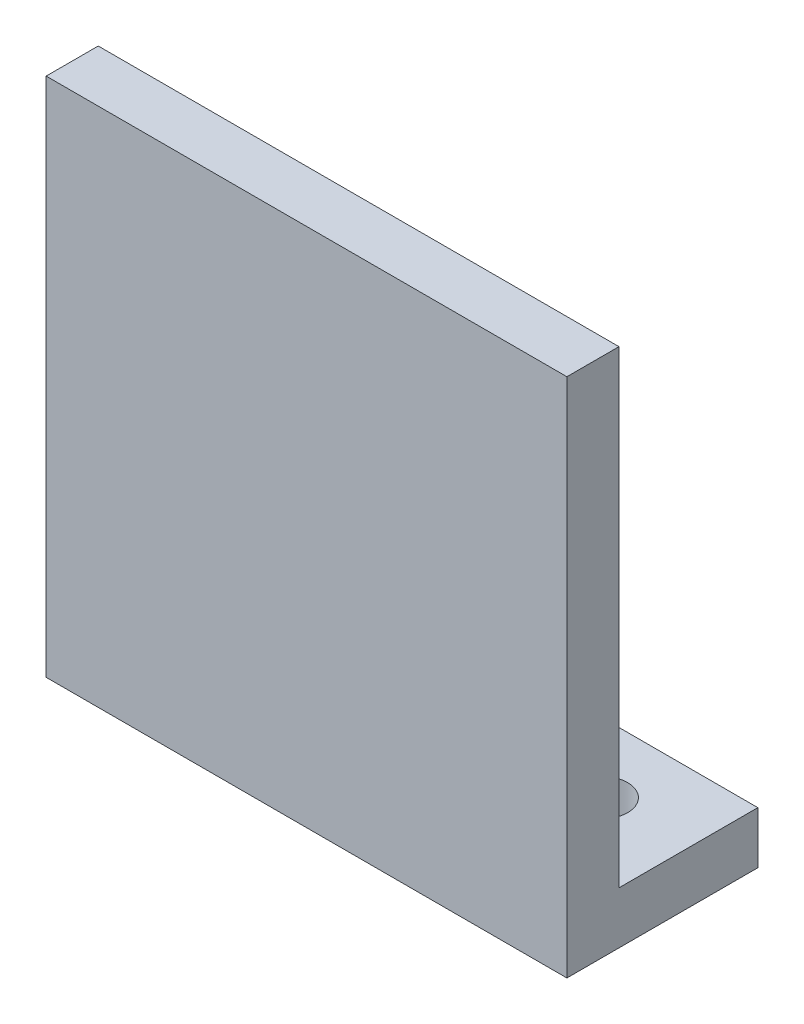
SolidWorks part; units mm, degrees
ref_plane "前视基准面" through (0, 0, 0) normal (0, 0, 1) x (1, 0, 0)
ref_plane "上视基准面" through (0, 0, 0) normal (0, 1, 0) x (1, 0, 0)
ref_plane "右视基准面" through (0, 0, 0) normal (1, 0, 0) x (0, 0, -1)
sketch "草图1" plane through (0, 0, 0) normal (0, 0, 1) x (1, 0, 0)
  line L1 (-15, -15) -> (15, -15)
  line L2 (-15, -15) -> (-15, 15)
  line L3 (-15, 15) -> (15, 15)
  line L4 (15, -15) -> (15, 15)
  line L5 (-15, -15) -> (15, 15) construction
  line L6 (-15, 15) -> (15, -15) construction
  point P0 (0, 0)
  dimension "D1" = 30
  dimension "D2" = 30
extrude "凸台-拉伸1" add sketch "草图1" along normal blind 3 contours L2 L3 L4 L1
sketch "草图2" plane through (0, 0, 0) normal (0, 0, -1) x (-1, 0, 0)
  line L1 (-15, -12) -> (15, -12)
  line L2 (-15, -12) -> (-15, -15)
  line L3 (-15, -15) -> (15, -15)
  line L4 (15, -12) -> (15, -15)
  line L5 (-15, -12) -> (15, -15) construction
  line L6 (-15, -15) -> (15, -12) construction
  point P0 (0, -13.5)
  dimension "D1" = 3
extrude "凸台-拉伸2" add sketch "草图2" along normal blind 8
sketch "草图3" plane through (0, 0, 0) normal (0, 0, -1) x (-1, 0, 0)
  text T0 "交" font "宋体" height in points 48
extrude "凸台-拉伸3" add sketch "草图3" along normal blind 2
sketch "草图4" plane through (0, -12, 0) normal (0, 1, 0) x (1, 0, 0)
  line L0 (0, 8) -> (0, -6.8565) construction
  line L1 (-15, 8) -> (15, 8) construction
  circle A0 centre (-10, 4) radius 1.5
  circle A1 centre (10, 4) radius 1.5
  dimension "D1" = 3
  dimension "D2" = 20
extrude "切除-拉伸1" cut sketch "草图4" against normal through all
